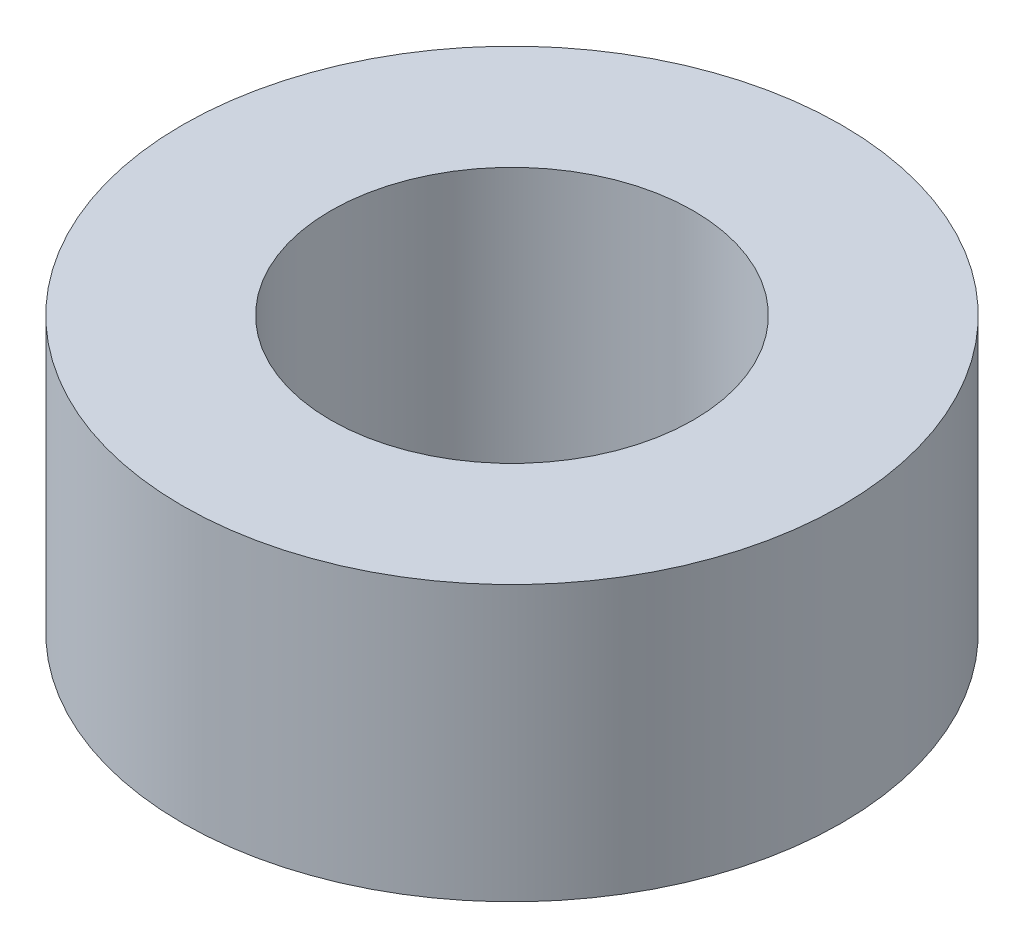
SolidWorks part; units mm, degrees
ref_plane "前视基准面" through (0, 0, 0) normal (0, 0, 1) x (1, 0, 0)
ref_plane "上视基准面" through (0, 0, 0) normal (0, 1, 0) x (1, 0, 0)
ref_plane "右视基准面" through (0, 0, 0) normal (1, 0, 0) x (0, 0, -1)
sketch "草图1" plane through (0, 0, 0) normal (0, 1, 0) x (1, 0, 0)
  circle A0 centre (0, 0) radius 1.65
  circle A1 centre (0, 0) radius 3
  dimension "D1" = 6
  dimension "D2" = 3.3
extrude "凸台-拉伸1" add sketch "草图1" along normal blind 2.5
